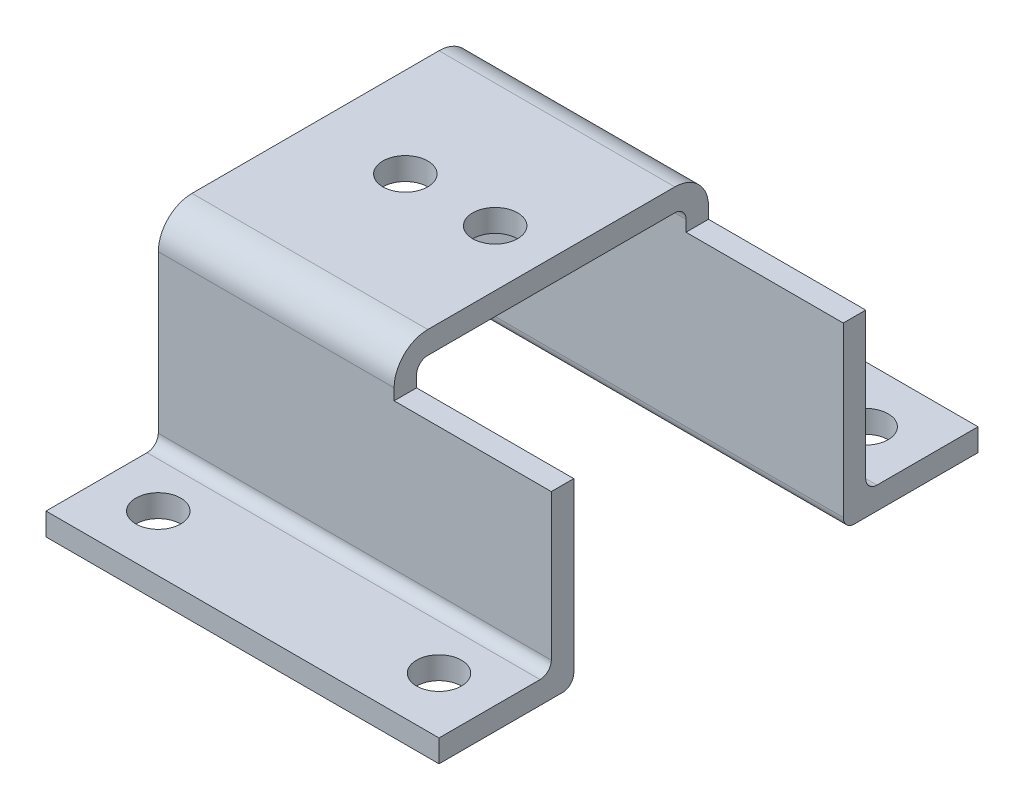
SolidWorks part; units mm, degrees
material "Alloy Steel"
ref_plane "Front Plane" through (0, 0, 0) normal (0, 0, 1) x (1, 0, 0)
ref_plane "Top Plane" through (0, 0, 0) normal (0, 1, 0) x (1, 0, 0)
ref_plane "Right Plane" through (0, 0, 0) normal (1, 0, 0) x (0, 0, -1)
sketch "Sketch1" plane through (0, 0, 0) normal (1, 0, 0) x (0, 0, -1)
  line L0 (0, 0) -> (11, 0)
  line L1 (12, 1) -> (12, 17)
  line L2 (13, 18) -> (35, 18)
  line L3 (36, 17) -> (36, 1)
  line L4 (37, 0) -> (48, 0)
  line L5 (24, 18) -> (24, -1.3286) construction
  line L6 (0, 2) -> (9, 2)
  line L7 (10, 3) -> (10, 17)
  line L8 (13, 20) -> (35, 20)
  line L9 (38, 17) -> (38, 3)
  line L10 (39, 2) -> (48, 2)
  line L11 (0, 2) -> (0, 0)
  line L12 (48, 2) -> (48, 0)
  line L13 (0, 2) -> (10, 2) construction
  line L14 (10, 2) -> (10, 17) construction
  line L15 (38, 17) -> (38, 2) construction
  line L16 (38, 2) -> (48, 2) construction
  arc A0 (37, 0) -> (36, 1) centre (37, 1) cw
  arc A1 (12, 1) -> (11, 0) centre (11, 1) cw
  arc A2 (36, 17) -> (35, 18) centre (35, 17) ccw
  arc A3 (13, 18) -> (12, 17) centre (13, 17) ccw
  arc A4 (38, 3) -> (39, 2) centre (39, 3) ccw
  arc A5 (13, 20) -> (10, 17) centre (13, 17) ccw
  arc A6 (38, 17) -> (35, 20) centre (35, 17) ccw
  arc A8 (9, 2) -> (10, 3) centre (9, 3) ccw
  arc A9 (10, 2) -> (10, 2) centre (10, 2) cw construction
  arc A10 (38, 2) -> (38, 2) centre (38, 2) cw construction
  point P15 (36, 18)
  point P18 (12, 18)
  dimension "D5" = 1
  dimension "D7" = 1
  dimension "D1" = 48
  dimension "D2" = 24
  dimension "D3" = 18
  dimension "D4" = 24
  dimension "D6" = 2
extrude "Boss-Extrude1" add sketch "Sketch1" along normal mid plane 35
sketch "Sketch3" plane through (17.5, 0, 0) normal (1, 0, 0) x (0, 0, -1)
  line L0 (10, 16) -> (38, 16)
  line L1 (38, 16) -> (38, 17)
  line L2 (10, 16) -> (10, 17)
  line L12 (0, 2) -> (0, 0)
  line L13 (0, 0) -> (11, 0)
  line L14 (12, 1) -> (12, 17)
  line L15 (13, 18) -> (35, 18)
  line L16 (36, 17) -> (36, 1)
  line L17 (37, 0) -> (48, 0)
  line L18 (48, 0) -> (48, 2)
  line L19 (48, 2) -> (39, 2)
  line L20 (38, 3) -> (38, 17)
  line L21 (35, 20) -> (13, 20)
  line L22 (10, 17) -> (10, 3)
  line L23 (9, 2) -> (0, 2)
  line L24 (0, 2) -> (0, 0)
  line L25 (0, 0) -> (11, 0)
  line L26 (12, 1) -> (12, 17)
  line L27 (13, 18) -> (35, 18)
  line L28 (36, 17) -> (36, 1)
  line L29 (37, 0) -> (48, 0)
  line L30 (48, 0) -> (48, 2)
  line L31 (48, 2) -> (39, 2)
  line L32 (38, 3) -> (38, 17)
  line L33 (35, 20) -> (13, 20)
  line L34 (10, 17) -> (10, 3)
  line L35 (9, 2) -> (0, 2)
  arc A8 (11, 0) -> (12, 1) centre (11, 1) ccw
  arc A9 (13, 18) -> (12, 17) centre (13, 17) ccw
  arc A10 (36, 17) -> (35, 18) centre (35, 17) ccw
  arc A11 (36, 1) -> (37, 0) centre (37, 1) ccw
  arc A12 (38, 3) -> (39, 2) centre (39, 3) ccw
  arc A13 (38, 17) -> (35, 20) centre (35, 17) ccw
  arc A14 (13, 20) -> (10, 17) centre (13, 17) ccw
  arc A15 (9, 2) -> (10, 3) centre (9, 3) ccw
  arc A16 (11, 0) -> (12, 1) centre (11, 1) ccw
  arc A17 (13, 18) -> (12, 17) centre (13, 17) ccw
  arc A18 (36, 17) -> (35, 18) centre (35, 17) ccw
  arc A19 (36, 1) -> (37, 0) centre (37, 1) ccw
  arc A20 (38, 3) -> (39, 2) centre (39, 3) ccw
  arc A21 (38, 17) -> (35, 20) centre (35, 17) ccw
  arc A22 (13, 20) -> (10, 17) centre (13, 17) ccw
  arc A23 (9, 2) -> (10, 3) centre (9, 3) ccw
  dimension "D2" = 4
  dimension "D1" = 0
extrude "Cut-Extrude2" cut sketch "Sketch3" against normal blind 14 and the other way through all contours L2 L0 L1
sketch "Sketch4" plane through (0, 2, 0) normal (0, 1, 0) x (1, 0, 0)
  line L0 (17.5, 48) -> (17.5, 39) construction
  line L1 (-17.5, 48) -> (-17.5, 39) construction
  line L2 (3.5, 35) -> (3.5, 13) construction
  line L3 (-17.5, 24) -> (23.7656, 24) construction
  line L4 (-17.5, 35) -> (-17.5, 13) construction
  circle A0 centre (-12.5, 43) radius 2
  circle A1 centre (12.5, 43) radius 2
  point P12 (3.5, 24)
  dimension "D1" = 4
  dimension "D2" = 5
  dimension "D3" = 5
  dimension "D4" = 19
extrude "Cut-Extrude3" cut sketch "Sketch4" against normal through all both and the other way through all
sketch "Sketch6" plane through (0, 2, 0) normal (0, 1, 0) x (1, 0, 0)
  line L0 (17.5, 9) -> (17.5, 0) construction
  line L1 (-17.5, 35) -> (-17.5, 13) construction
  circle A0 centre (-12.5, 5) radius 2
  circle A1 centre (12.5, 5) radius 2
  circle A2 centre (-9.5, 24) radius 2
  circle A3 centre (-1.5, 24) radius 2
  dimension "D1" = 4
  dimension "D8" = 4
  dimension "D2" = 25
  dimension "D3" = 5
  dimension "D4" = 38
  dimension "D5" = 8
  dimension "D6" = 16
  dimension "D7" = 19
extrude "Cut-Extrude5" cut sketch "Sketch6" along direction (0, -1, 0) on the side of the normal through all both and the other way through all
